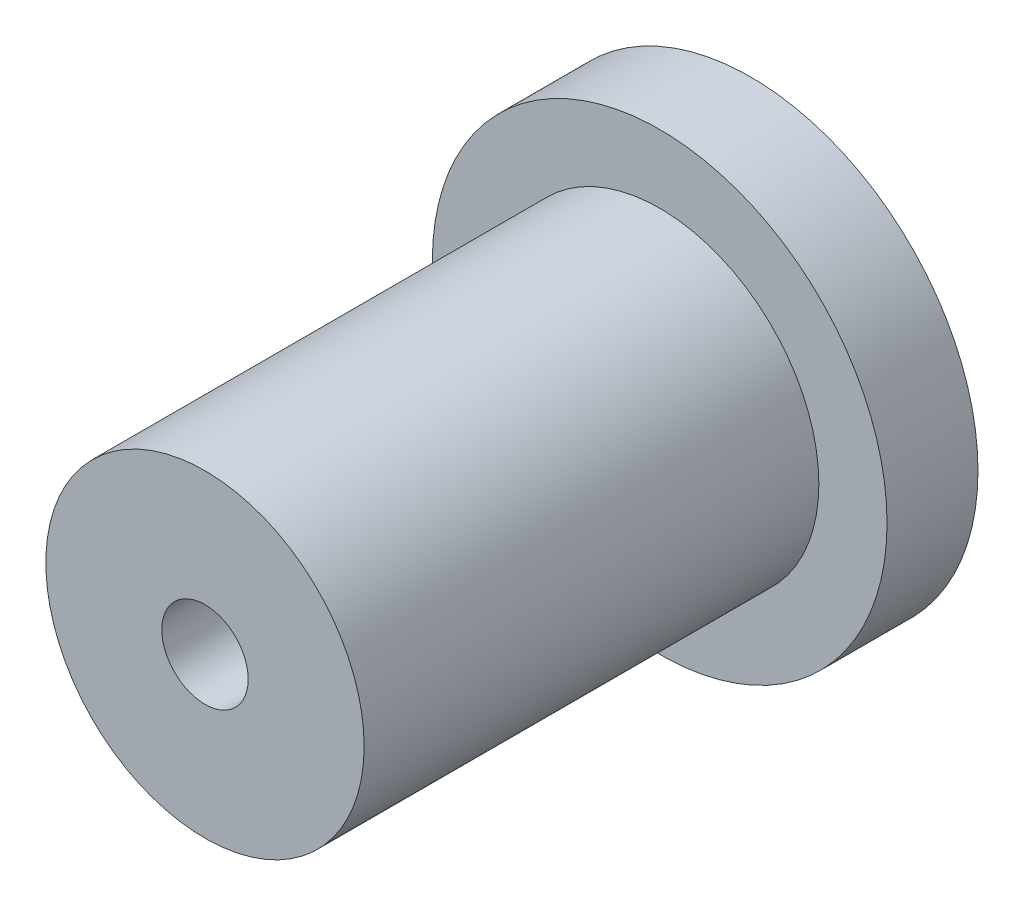
SolidWorks part; units mm, degrees
ref_plane "Front Plane" through (0, 0, 0) normal (0, 0, 1) x (1, 0, 0)
ref_plane "Top Plane" through (0, 0, 0) normal (0, 1, 0) x (1, 0, 0)
ref_plane "Right Plane" through (0, 0, 0) normal (1, 0, 0) x (0, 0, -1)
sketch "Sketch2" plane through (0, 0, 0) normal (0, 0, 1) x (1, 0, 0)
  circle A0 centre (0, 0) radius 5
extrude "Boss-Extrude1" add sketch "Sketch2" along normal blind 2 contours A0
sketch "Sketch3" plane through (0, 0, 2) normal (0, 0, 1) x (1, 0, 0)
  circle A0 centre (0, 0) radius 3.5
extrude "Boss-Extrude2" add sketch "Sketch3" along normal blind 10 contours A0
sketch "Sketch4" plane through (0, 0, 12) normal (0, 0, 1) x (1, 0, 0)
  circle A0 centre (0, 0) radius 0.95
extrude "Cut-Extrude1" cut sketch "Sketch4" against normal through all
